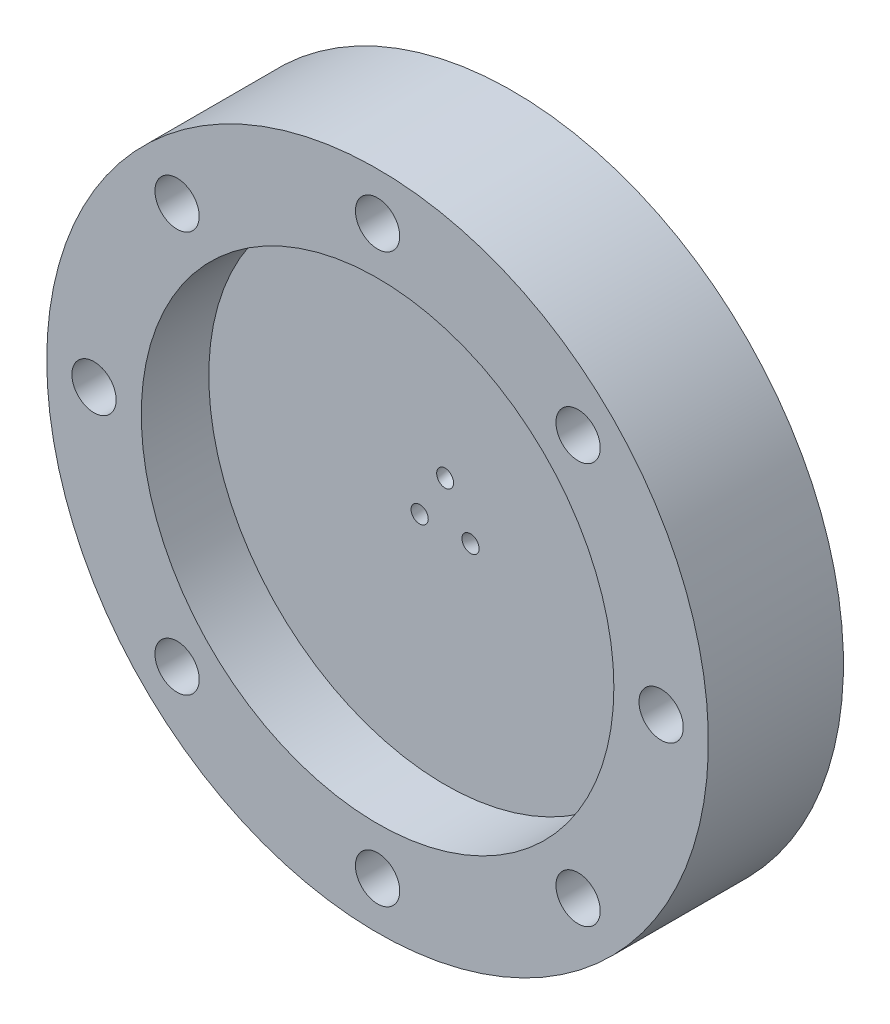
SolidWorks part; units mm, degrees
material "PLA (Polylactic Acid)"
ref_plane "Front Plane" through (0, 0, 0) normal (0, 0, 1) x (1, 0, 0)
ref_plane "Top Plane" through (0, 0, 0) normal (0, 1, 0) x (1, 0, 0)
ref_plane "Right Plane" through (0, 0, 0) normal (1, 0, 0) x (0, 0, -1)
sketch "Sketch2" plane through (0, 0, -1.7131) normal (0, 0, -1) x (-1, 0, 0)
  circle A0 centre (0, 0) radius 31.115
  dimension "D1" = 62.23
extrude "Boss-Extrude1" add sketch "Sketch2" along normal blind 12.7
sketch "Sketch3" plane through (0, 0, -14.4131) normal (0, 0, -1) x (-1, 0, 0)
  circle A0 centre (0, 26.67) radius 2.0828
  circle A1 centre (0, 0) radius 26.67 construction
  circle A2 centre (18.8585, 18.8585) radius 2.0828
  circle A4 centre (26.67, 0) radius 2.0828
  circle A5 centre (18.8585, -18.8585) radius 2.0828
  circle A6 centre (0, -26.67) radius 2.0828
  circle A7 centre (-18.8585, -18.8585) radius 2.0828
  circle A8 centre (-26.67, 0) radius 2.0828
  circle A9 centre (-18.8585, 18.8585) radius 2.0828
  point P23 (0, 0)
  dimension "D1" = 53.34
  dimension "D2" = 4.1656
  dimension "D3" = 8
extrude "Cut-Extrude3" cut sketch "Sketch3" against normal up to surface (12.7 mm away) up to face at (-31.115, 0, -1.7131)
sketch "Sketch4" plane through (0, 0, -1.7131) normal (0, 0, 1) x (1, 0, 0)
  circle A0 centre (0, 0) radius 22.225
  dimension "D1" = 44.45
extrude "Cut-Extrude2" cut sketch "Sketch4" against normal blind 6.35
sketch "Sketch6" plane through (0, 0, 0) normal (1, 0, 0) x (0, 0, -1)
  line L0 (-69.0368, 0) -> (69.0368, 0) construction
  line L1 (9.9681, 0) -> (9.9681, 6.35)
  line L2 (9.9681, 6.35) -> (12.5081, 6.35)
  line L3 (12.5081, 6.35) -> (12.5081, 2.0828)
  line L4 (12.5081, 2.0828) -> (14.4131, 2.0828)
  line L5 (14.4131, 2.0828) -> (14.4131, 0)
  line L6 (14.4131, 0) -> (9.9681, 0)
  line L7 (14.4131, -26.67) -> (14.4131, 26.67) construction
  line L8 (1.7131, 31.115) -> (1.7131, -31.115) construction
  point P3 (8.0631, 0)
  point P5 (0, 0)
  dimension "D1" = 6.35
  dimension "D2" = 1.905
  dimension "D3" = 6.35
  dimension "D4" = 1.905
revolve "Cut-Revolve2" cut sketch "Sketch6" angle 360 about L0
sketch "Sketch7" plane through (0, 0, 0) normal (1, 0, 0) x (0, 0, -1)
  line L0 (1.7131, 0) -> (-4.6369, 0) construction
  line L1 (1.7131, 31.115) -> (1.7131, -31.115) construction
  line L2 (9.9681, 6.35) -> (9.9681, -6.35) construction
  line L3 (9.9681, 3.175) -> (-4.6369, 0) construction
  dimension "D1" = 6.35
  dimension "D2" = 3.175
ref_plane "Plane1" through (0, 0, 4.6369) normal (0, -0.2124, 0.9772) x (1, 0, 0)
sketch "Sketch8" plane through (0, 0, 4.6369) normal (0, -0.2124, 0.9772) x (1, 0, 0)
  circle A0 centre (0, 0) radius 0.7937
  dimension "D1" = 1.5875
extrude "Cut-Extrude4" cut sketch "Sketch8" against normal up to surface (14.7736 mm away)
pattern_circular "CirPattern1" count 3 over 360 about axis through (0, 0, -1.7131) along (0, 0, 1) of "Cut-Extrude4"
